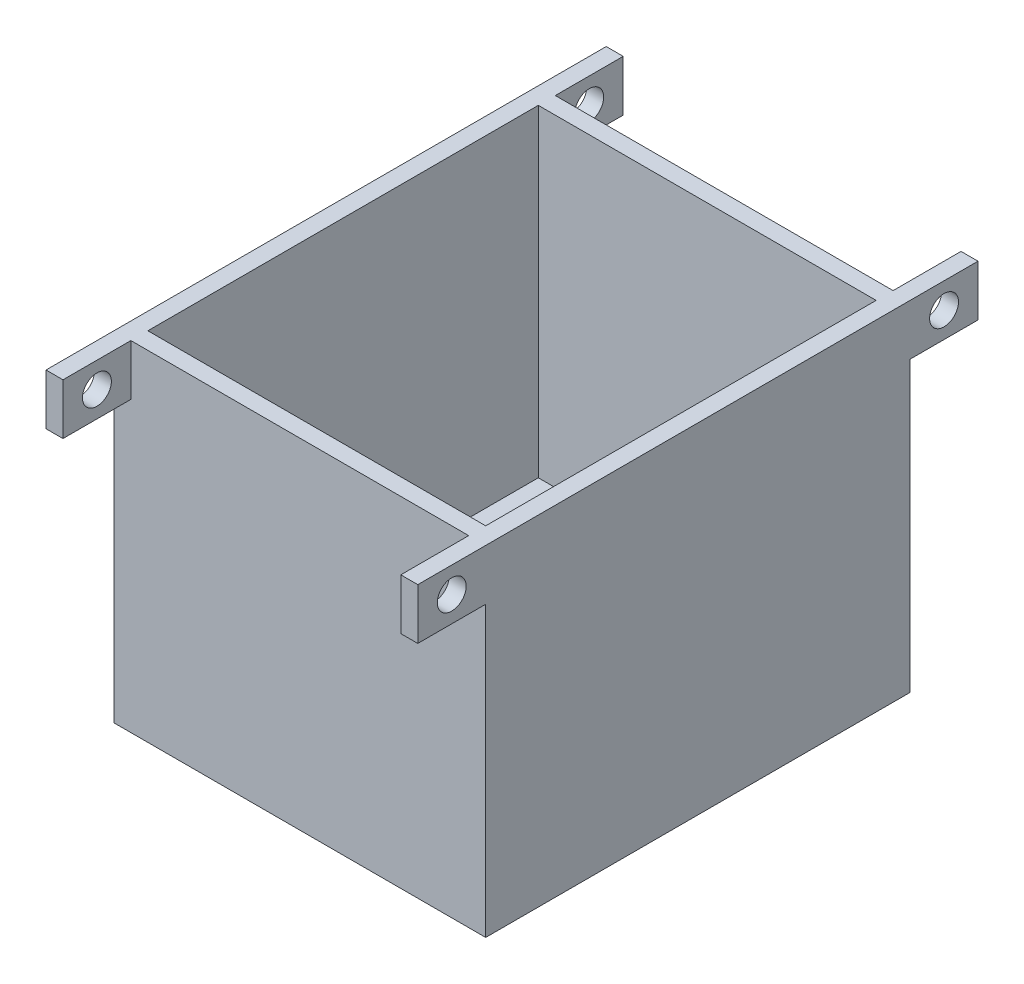
SolidWorks part; units mm, degrees
material "6061 Alloy"
ref_plane "Front Plane" through (0, 0, 0) normal (0, 0, 1) x (1, 0, 0)
ref_plane "Top Plane" through (0, 0, 0) normal (0, 1, 0) x (1, 0, 0)
ref_plane "Right Plane" through (0, 0, 0) normal (1, 0, 0) x (0, 0, -1)
sketch "Sketch1" plane through (0, 0, 0) normal (0, 1, 0) x (1, 0, 0)
  line L1 (-27.813, 31.75) -> (27.813, 31.75)
  line L2 (-27.813, 31.75) -> (-27.813, -31.75)
  line L3 (-27.813, -31.75) -> (27.813, -31.75)
  line L4 (27.813, 31.75) -> (27.813, -31.75)
  line L5 (-27.813, 31.75) -> (27.813, -31.75) construction
  line L6 (-27.813, -31.75) -> (27.813, 31.75) construction
  point P0 (0, 0)
extrude "Boss-Extrude1" add sketch "Sketch1" against normal blind 50.8
sketch "Sketch2" plane through (0, 0, 0) normal (0, 1, 0) x (1, 0, 0)
  line L1 (25.273, 29.21) -> (-25.273, 29.21)
  line L2 (25.273, 29.21) -> (25.273, -29.21)
  line L3 (25.273, -29.21) -> (-25.273, -29.21)
  line L4 (-25.273, 29.21) -> (-25.273, -29.21)
  line L5 (25.273, 29.21) -> (-25.273, -29.21) construction
  line L6 (25.273, -29.21) -> (-25.273, 29.21) construction
  point P0 (0, 0)
extrude "Cut-Extrude1" cut sketch "Sketch2" against normal blind 48.26
ref_plane "Plane1" through (27.813, 0, 0) normal (1, 0, 0) x (0, 0, -1)
sketch "Sketch3" plane through (27.813, 0, 0) normal (1, 0, 0) x (0, 0, -1)
  line L0 (-31.75, 0) -> (-41.91, 0)
  line L1 (-41.91, 0) -> (-41.91, -7.62)
  line L2 (-41.91, -7.62) -> (-31.75, -7.62)
  line L3 (-31.75, -50.8) -> (-31.75, 0) construction
  line L4 (-31.75, -7.62) -> (-31.75, 0)
  line L5 (-41.91, -3.81) -> (-31.75, -3.81) construction
  line L6 (-36.83, 0) -> (-36.83, -7.62) construction
  circle A0 centre (-36.83, -3.81) radius 2.159
extrude "Boss-Extrude2" add sketch "Sketch3" against normal blind 2.54
mirror "Mirror1" about plane through (0, 0, 0) normal (0, 0, 1) of "Boss-Extrude2"
mirror "Mirror2" about plane through (0, 0, 0) normal (1, 0, 0) of "Mirror1", "Boss-Extrude2"
